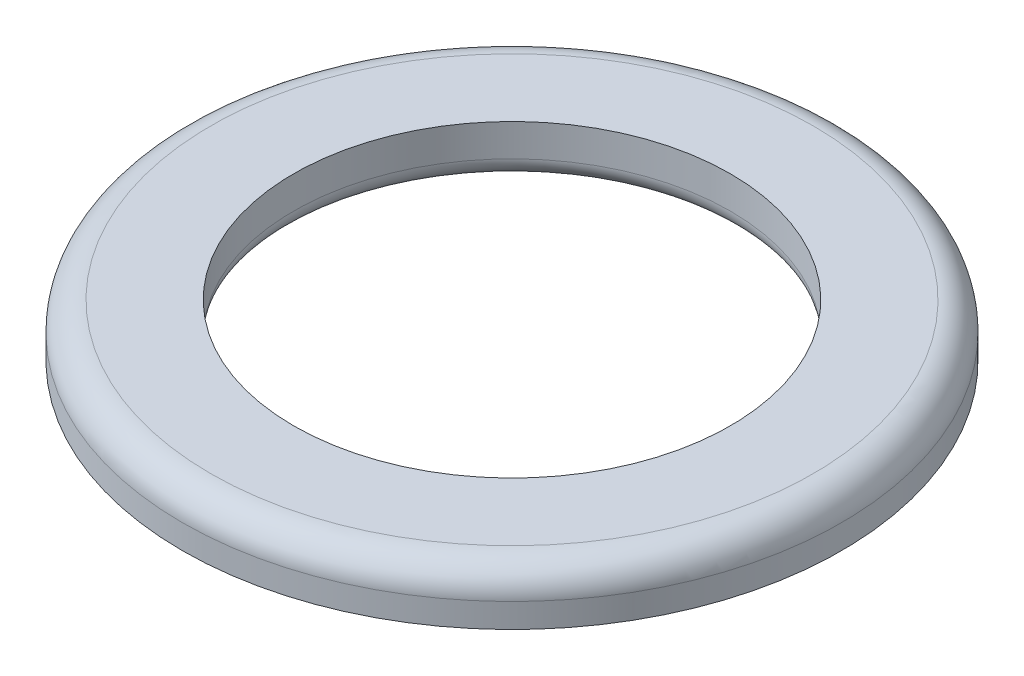
SolidWorks part; units mm, degrees
ref_plane "Front Plane" through (0, 0, 0) normal (0, 0, 1) x (1, 0, 0)
ref_plane "Top Plane" through (0, 0, 0) normal (0, 1, 0) x (1, 0, 0)
ref_plane "Right Plane" through (0, 0, 0) normal (1, 0, 0) x (0, 0, -1)
sketch "Sketch1" plane through (0, 0, 0) normal (0, 1, 0) x (1, 0, 0)
  circle A0 centre (0, 0) radius 8.15
  circle A1 centre (0, 0) radius 5.4
  dimension "D1" = 16.3
  dimension "D2" = 10.8
extrude "Boss-Extrude1" add sketch "Sketch1" along normal blind 1.3
fillet "Fillet3" radius 0.7 1 edges at (0, 1.3, 8.15)
fillet "Fillet4" radius 0.5 1 edges at (0, 0, 5.4)
